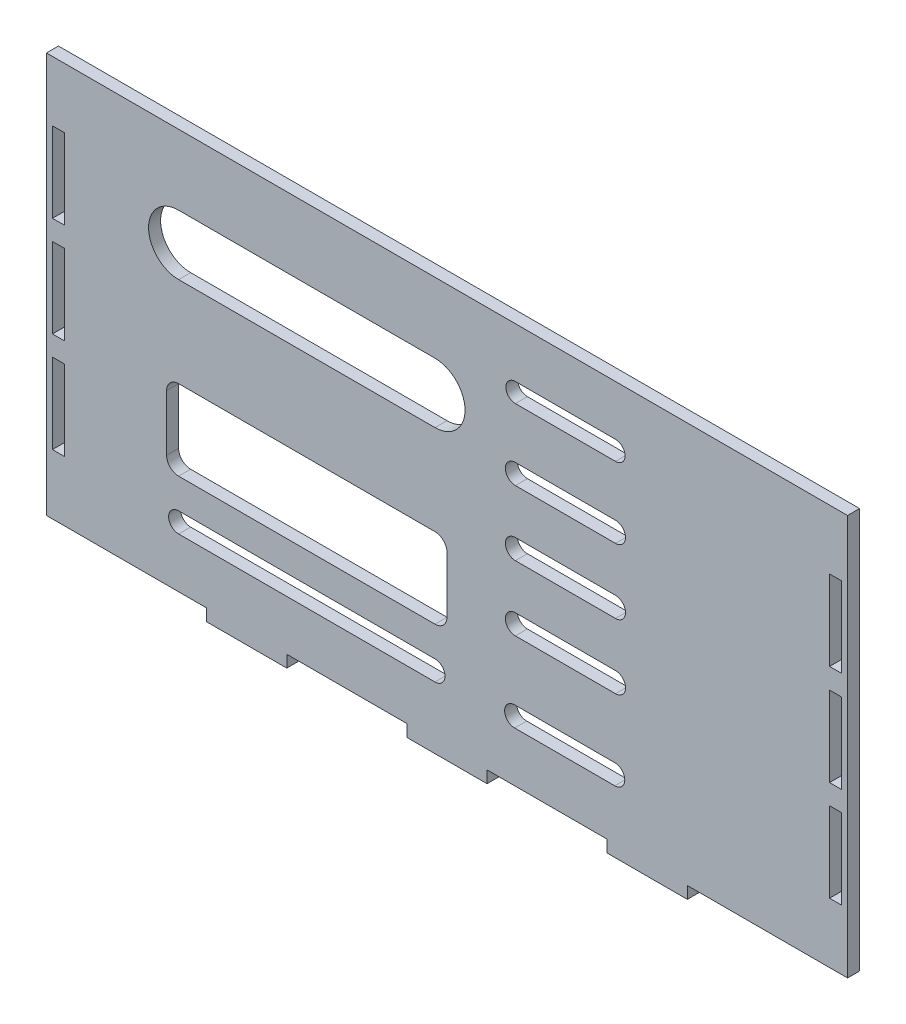
SolidWorks part; units mm, degrees
ref_plane "Front Plane" through (0, 0, 0) normal (0, 0, 1) x (1, 0, 0)
ref_plane "Top Plane" through (0, 0, 0) normal (0, 1, 0) x (1, 0, 0)
ref_plane "Right Plane" through (0, 0, 0) normal (1, 0, 0) x (0, 0, -1)
sketch "Sketch1" plane through (0, 0, 0) normal (0, 0, 1) x (1, 0, 0)
  line L0 (-100, -50) -> (-60, -50) construction
  line L1 (-100, -50) -> (-60, -50)
  line L2 (-100, -50) -> (-100, 50)
  line L3 (-100, 50) -> (100, 50)
  line L4 (100, -50) -> (100, 50)
  line L5 (-100, -50) -> (100, 50) construction
  line L6 (-100, 50) -> (100, -50) construction
  line L7 (-40, -50) -> (-10, -50) construction
  line L8 (10, -50) -> (40, -50) construction
  line L9 (60, -50) -> (100, -50) construction
  line L10 (-40, -50) -> (-10, -50)
  line L11 (-60, -53) -> (-40, -53)
  line L12 (-60, -53) -> (-60, -50)
  line L14 (-40, -53) -> (-40, -50)
  line L15 (-100, -50) -> (-100, -25) construction
  line L16 (-100, -25) -> (-70, -25) construction
  line L17 (-10, -53) -> (10, -53)
  line L18 (-10, -53) -> (-10, -50)
  line L20 (10, -53) -> (10, -50)
  line L21 (-100, 50) -> (-97, 50) construction
  line L22 (-67, -25) -> (-3, -25)
  line L23 (40, -53) -> (60, -53)
  line L24 (40, -53) -> (40, -50)
  line L26 (60, -53) -> (60, -50)
  line L27 (-70, -22) -> (-70, -8)
  line L28 (-67, -5) -> (-3, -5)
  line L29 (10, -50) -> (40, -50)
  line L30 (60, -50) -> (100, -50)
  line L31 (0, -22) -> (0, -8)
  line L32 (-97, 50) -> (-97, 25) construction
  line L33 (-97, 25) -> (-97, 0) construction
  line L34 (-97, 0) -> (-97, -25) construction
  line L35 (-97, -25) -> (-97, -50) construction
  line L36 (100, 50) -> (97, 50) construction
  line L37 (-98.5, 35) -> (-95.5, 35)
  line L38 (-98.5, 35) -> (-98.5, 15)
  line L39 (-98.5, 15) -> (-95.5, 15)
  line L40 (-95.5, 35) -> (-95.5, 15)
  line L41 (-98.5, 35) -> (-95.5, 15) construction
  line L42 (-98.5, 15) -> (-95.5, 35) construction
  line L43 (-98.5, 10) -> (-95.5, 10)
  line L44 (-98.5, 10) -> (-98.5, -10)
  line L45 (-98.5, -10) -> (-95.5, -10)
  line L46 (-95.5, 10) -> (-95.5, -10)
  line L47 (-98.5, 10) -> (-95.5, -10) construction
  line L48 (-98.5, -10) -> (-95.5, 10) construction
  line L49 (-98.5, -15) -> (-95.5, -15)
  line L50 (-98.5, -15) -> (-98.5, -35)
  line L51 (-98.5, -35) -> (-95.5, -35)
  line L52 (-95.5, -15) -> (-95.5, -35)
  line L53 (-98.5, -15) -> (-95.5, -35) construction
  line L54 (-98.5, -35) -> (-95.5, -15) construction
  line L55 (97, 50) -> (97, 25.1134) construction
  line L56 (97, 25.1134) -> (97, 0) construction
  line L57 (97, 0) -> (97, -25) construction
  line L58 (97, -25) -> (97, -50) construction
  line L59 (17.0664, 35.1134) -> (42.0664, 35.1134) construction
  line L60 (95.5, 35.1134) -> (98.5, 35.1134)
  line L61 (95.5, 35.1134) -> (95.5, 15.1134)
  line L62 (95.5, 15.1134) -> (98.5, 15.1134)
  line L63 (98.5, 35.1134) -> (98.5, 15.1134)
  line L64 (95.5, 35.1134) -> (98.5, 15.1134) construction
  line L65 (95.5, 15.1134) -> (98.5, 35.1134) construction
  line L66 (95.5, 10) -> (98.5, 10)
  line L67 (95.5, 10) -> (95.5, -10)
  line L68 (95.5, -10) -> (98.5, -10)
  line L69 (98.5, 10) -> (98.5, -10)
  line L70 (95.5, 10) -> (98.5, -10) construction
  line L71 (95.5, -10) -> (98.5, 10) construction
  line L72 (95.5, -15) -> (98.5, -15)
  line L73 (95.5, -15) -> (95.5, -35)
  line L74 (95.5, -35) -> (98.5, -35)
  line L75 (98.5, -15) -> (98.5, -35)
  line L76 (95.5, -15) -> (98.5, -35) construction
  line L77 (95.5, -35) -> (98.5, -15) construction
  line L78 (17.0664, 17.5006) -> (42.0664, 17.5006) construction
  line L79 (17.0664, 37.5) -> (42.0664, 37.5)
  line L80 (17.0664, 32.7268) -> (42.0664, 32.7268)
  line L81 (17.0664, -15) -> (42.0664, -15) construction
  line L82 (17.0664, 20.0006) -> (42.0664, 20.0006)
  line L83 (17.0664, 15.0006) -> (42.0664, 15.0006)
  line L84 (17.0664, 1.2662) -> (42.0664, 1.2662) construction
  line L85 (17.0664, 3.7662) -> (42.0664, 3.7662)
  line L86 (17.0664, -1.2338) -> (42.0664, -1.2338)
  line L87 (-67, 25) -> (-3, 25) construction
  line L90 (16.8826, -35) -> (41.8826, -35) construction
  line L91 (16.8826, -32.5) -> (41.8826, -32.5)
  line L92 (16.8826, -37.5) -> (41.8826, -37.5)
  line L93 (17.0664, -12.5) -> (42.0664, -12.5)
  line L94 (17.0664, -17.5) -> (42.0664, -17.5)
  line L97 (-67, 32.5) -> (-3, 32.5)
  line L98 (-67, 17.5) -> (-3, 17.5)
  line L99 (-67, -35) -> (-3, -35) construction
  line L100 (-67, -32.5) -> (-3, -32.5)
  line L101 (-67, -37.5) -> (-3, -37.5)
  arc A0 (-70, -8) -> (-67, -5) centre (-67, -8) cw
  arc A1 (-3, -5) -> (0, -8) centre (-3, -8) cw
  arc A2 (-3, -25) -> (0, -22) centre (-3, -22) ccw
  arc A3 (-70, -22) -> (-67, -25) centre (-67, -22) ccw
  arc A4 (17.0664, 37.5) -> (17.0664, 32.7268) centre (17.0664, 35.1134) ccw
  arc A5 (42.0664, 32.7268) -> (42.0664, 37.5) centre (42.0664, 35.1134) ccw
  arc A6 (17.0664, 20.0006) -> (17.0664, 15.0006) centre (17.0664, 17.5006) ccw
  arc A7 (42.0664, 15.0006) -> (42.0664, 20.0006) centre (42.0664, 17.5006) ccw
  arc A8 (17.0664, 3.7662) -> (17.0664, -1.2338) centre (17.0664, 1.2662) ccw
  arc A9 (42.0664, -1.2338) -> (42.0664, 3.7662) centre (42.0664, 1.2662) ccw
  arc A12 (16.8826, -32.5) -> (16.8826, -37.5) centre (16.8826, -35) ccw
  arc A13 (41.8826, -37.5) -> (41.8826, -32.5) centre (41.8826, -35) ccw
  arc A14 (17.0664, -12.5) -> (17.0664, -17.5) centre (17.0664, -15) ccw
  arc A15 (42.0664, -17.5) -> (42.0664, -12.5) centre (42.0664, -15) ccw
  arc A18 (-67, 32.5) -> (-67, 17.5) centre (-67, 25) ccw
  arc A19 (-3, 17.5) -> (-3, 32.5) centre (-3, 25) ccw
  arc A20 (-67, -32.5) -> (-67, -37.5) centre (-67, -35) ccw
  arc A21 (-3, -37.5) -> (-3, -32.5) centre (-3, -35) ccw
  point P0 (0, 0)
  point P17 (-70, -5)
  point P28 (0, -5)
  point P72 (29.5664, 35.1134)
  point P79 (29.5664, 17.5006)
  point P84 (29.5664, 1.2662)
  point P93 (29.5664, -15)
  point P98 (29.3826, -35)
  point P105 (-35, 25)
  point P112 (-35, -35)
  dimension "D12" = 3
  dimension "D13" = 3
  dimension "D14" = 3
  dimension "D15" = 3
  dimension "D1" = 100
  dimension "D2" = 200
  dimension "D3" = 20
  dimension "D4" = 20
  dimension "D5" = 20
  dimension "D6" = 3
  dimension "D7" = 3
  dimension "D8" = 3
  dimension "D9" = 70
  dimension "D10" = 20
  dimension "D11" = 25
  dimension "D16" = 3
  dimension "D17" = 25
  dimension "D18" = 25
  dimension "D19" = 25
  dimension "D20" = 25
  dimension "D21" = 3
extrude "Boss-Extrude1" add sketch "Sketch1" along normal blind 3
